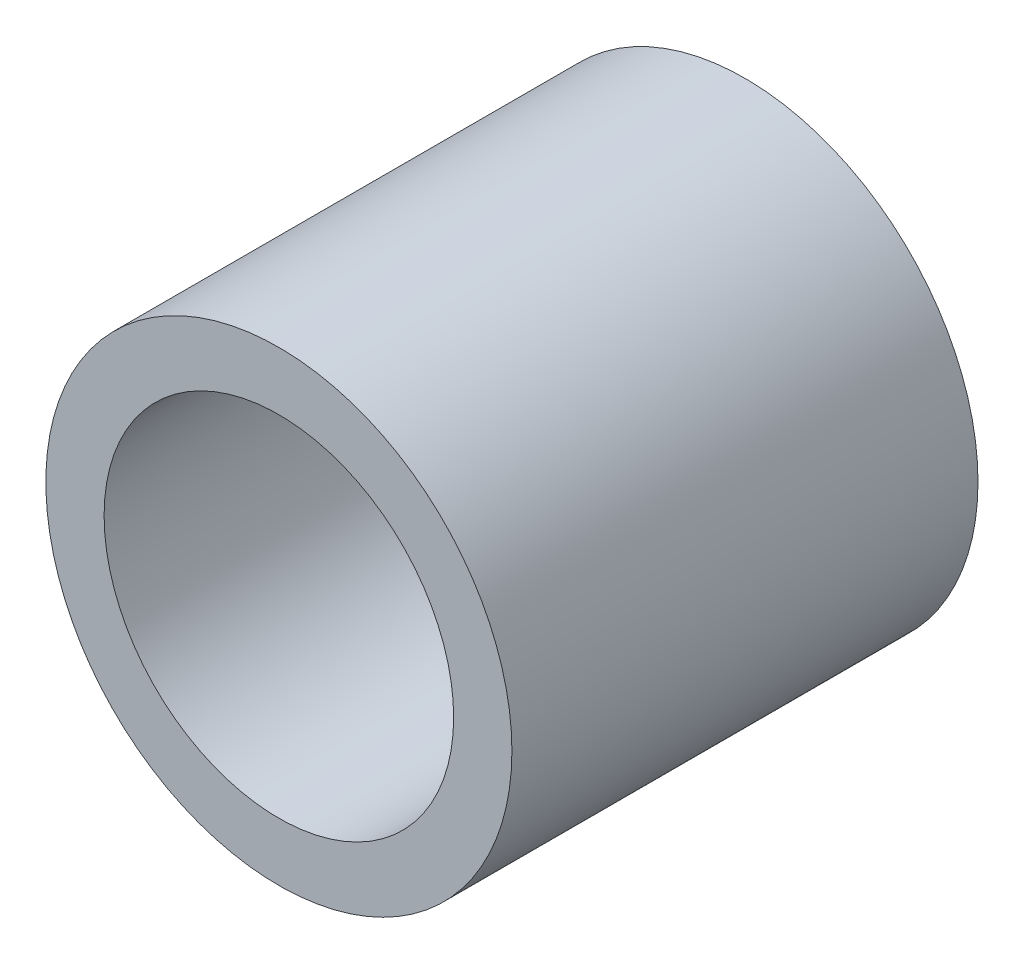
SolidWorks part; units mm, degrees
ref_plane "Front Plane" through (0, 0, 0) normal (0, 0, 1) x (1, 0, 0)
ref_plane "Top Plane" through (0, 0, 0) normal (0, 1, 0) x (1, 0, 0)
ref_plane "Right Plane" through (0, 0, 0) normal (1, 0, 0) x (0, 0, -1)
sketch "Sketch1" plane through (0, 0, 0) normal (0, 0, 1) x (1, 0, 0)
  circle A0 centre (0, 0) radius 12.7
  circle A1 centre (0, 0) radius 9.525
  dimension "D1" = 25.4
  dimension "D2" = 19.05
extrude "Boss-Extrude1" add sketch "Sketch1" along normal mid plane 25.4
